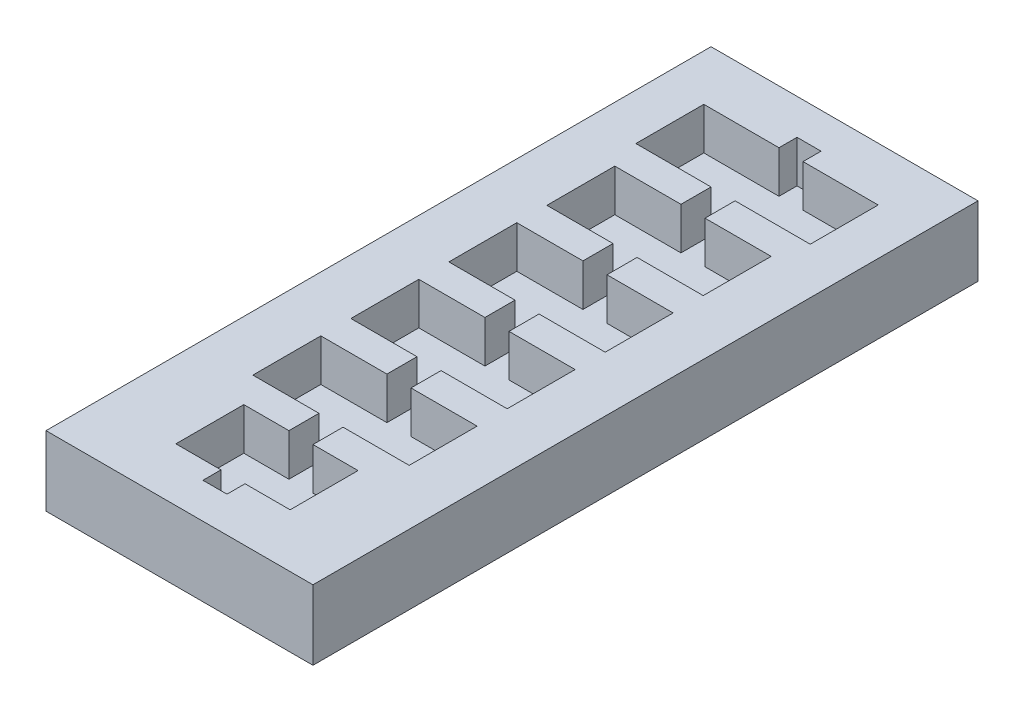
SolidWorks part; units mm, degrees
ref_plane "Спереди" through (0, 0, 0) normal (0, 0, 1) x (1, 0, 0)
ref_plane "Сверху" through (0, 0, 0) normal (0, 1, 0) x (1, 0, 0)
ref_plane "Справа" through (0, 0, 0) normal (1, 0, 0) x (0, 0, -1)
sketch "Эскиз1" plane through (0, 0, 0) normal (0, 1, 0) x (1, 0, 0)
  line L1 (0, 0) -> (0, 1106)
  line L2 (0, 0) -> (444, 0)
  line L3 (444, 0) -> (444, 1106)
  line L4 (0, 1106) -> (444, 1106)
  dimension "D1" = 444
  dimension "D2" = 1106
extrude "Наполнитель" add sketch "Эскиз1" against normal blind 116 contours L2 L1 L4 L3
sketch "Эскиз2" plane through (0, 0, 0) normal (0, 1, 0) x (1, 0, 0)
  line L0 (222, 0) -> (222, 1106) construction
  line L1 (0, 0) -> (444, 0) construction
  line L2 (0, 1106) -> (444, 1106) construction
  line L3 (242, 1047) -> (202, 1047)
  line L4 (202, 1047) -> (202, 1017)
  line L5 (202, 1017) -> (77, 1017)
  line L6 (77, 1017) -> (77, 904)
  line L7 (77, 904) -> (202, 904)
  line L8 (202, 904) -> (202, 854)
  line L9 (202, 854) -> (92, 854)
  line L10 (92, 854) -> (92, 741)
  line L11 (92, 741) -> (202, 741)
  line L12 (202, 741) -> (202, 691)
  line L13 (202, 691) -> (92, 691)
  line L14 (92, 691) -> (92, 578)
  line L15 (92, 578) -> (202, 578)
  line L16 (202, 578) -> (202, 528)
  line L17 (202, 528) -> (92, 528)
  line L18 (92, 528) -> (92, 415)
  line L19 (92, 415) -> (202, 415)
  line L20 (202, 415) -> (202, 365)
  line L21 (202, 365) -> (92, 365)
  line L22 (92, 365) -> (92, 252)
  line L23 (92, 252) -> (202, 252)
  line L24 (202, 252) -> (202, 202)
  line L25 (202, 202) -> (127, 202)
  line L26 (127, 202) -> (127, 89)
  line L27 (127, 89) -> (202, 89)
  line L28 (202, 89) -> (202, 59)
  line L29 (202, 59) -> (242, 59)
  line L30 (202, 89) -> (202, 1017) construction
  line L31 (242, 89) -> (242, 1017) construction
  line L32 (242, 89) -> (242, 59)
  line L33 (317, 89) -> (242, 89)
  line L34 (317, 202) -> (317, 89)
  line L35 (242, 202) -> (317, 202)
  line L36 (242, 252) -> (242, 202)
  line L37 (352, 252) -> (242, 252)
  line L38 (352, 365) -> (352, 252)
  line L39 (242, 365) -> (352, 365)
  line L40 (242, 415) -> (242, 365)
  line L41 (352, 415) -> (242, 415)
  line L42 (352, 528) -> (352, 415)
  line L43 (242, 528) -> (352, 528)
  line L44 (242, 578) -> (242, 528)
  line L45 (352, 578) -> (242, 578)
  line L46 (352, 691) -> (352, 578)
  line L47 (242, 691) -> (352, 691)
  line L48 (242, 741) -> (242, 691)
  line L49 (352, 741) -> (242, 741)
  line L50 (352, 854) -> (352, 741)
  line L51 (242, 854) -> (352, 854)
  line L52 (242, 904) -> (242, 854)
  line L53 (367, 904) -> (242, 904)
  line L54 (367, 1017) -> (367, 904)
  line L55 (242, 1017) -> (367, 1017)
  line L56 (242, 1047) -> (242, 1017)
  point P7 (77, 960.5)
  point P37 (222, 59)
  point P60 (222, 1047)
  dimension "D1" = 30
  dimension "D2" = 50
  dimension "D3" = 113
  dimension "D5" = 290
  dimension "D6" = 260
  dimension "D7" = 260
  dimension "D8" = 260
  dimension "D9" = 260
  dimension "D10" = 190
  dimension "D11" = 20
  dimension "D12" = 59
  dimension "D13" = 59
extrude "Вырез-Вытянуть1" cut sketch "Эскиз2" against normal blind 70
